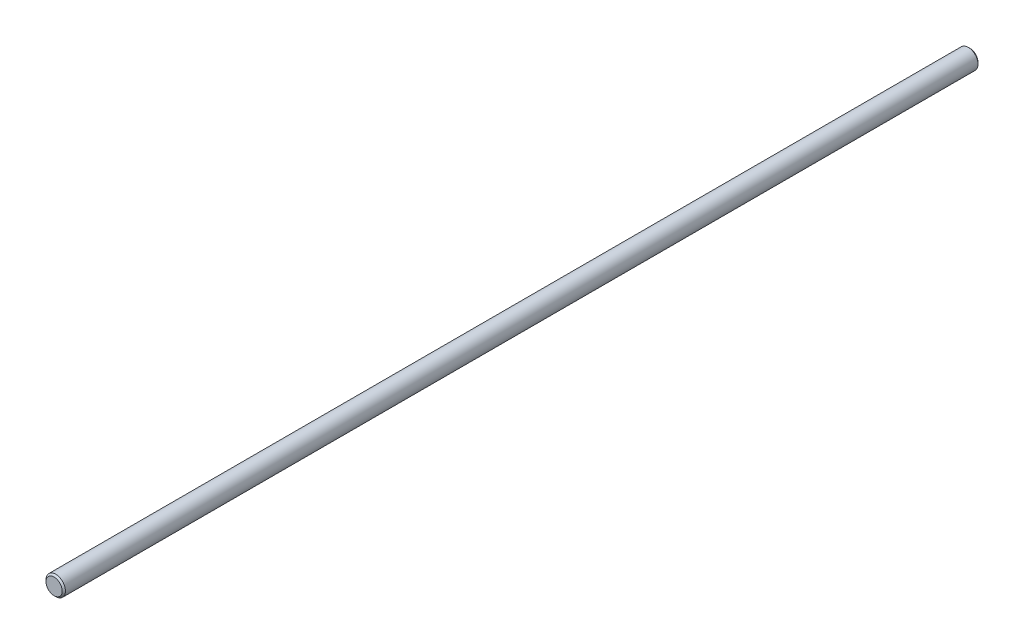
SolidWorks part; units mm, degrees
material "A286 Iron Base Superalloy"
ref_plane "Front Plane" through (0, 0, 0) normal (0, 0, 1) x (1, 0, 0)
ref_plane "Top Plane" through (0, 0, 0) normal (0, 1, 0) x (1, 0, 0)
ref_plane "Right Plane" through (0, 0, 0) normal (1, 0, 0) x (0, 0, -1)
sketch "Sketch1" plane through (0, 0, 0) normal (0, 0, 1) x (1, 0, 0)
  circle A0 centre (0, 0) radius 3
  dimension "D1" = 6
extrude "Boss-Extrude1" add sketch "Sketch1" along normal mid plane 282.5
chamfer "Chamfer1" distance 0.5 angle 45 2 edges at (3, 0, 141.25) (3, 0, -141.25)
